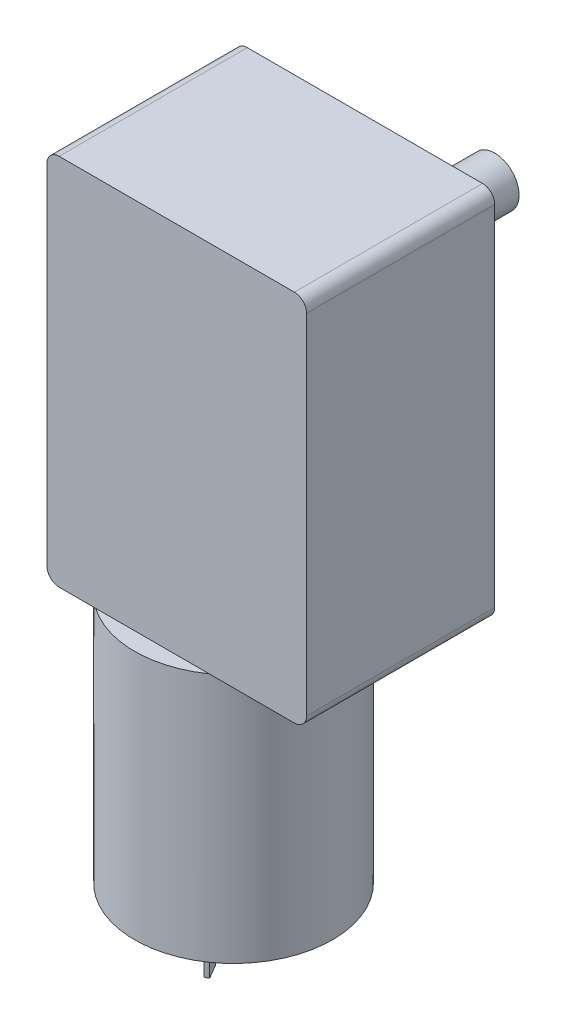
SolidWorks part; units mm, degrees
ref_plane "Front Plane" through (0, 0, 0) normal (0, 0, 1) x (1, 0, 0)
ref_plane "Top Plane" through (0, 0, 0) normal (0, 1, 0) x (1, 0, 0)
ref_plane "Right Plane" through (0, 0, 0) normal (1, 0, 0) x (0, 0, -1)
sketch "Sketch1" plane through (0, 0, 0) normal (0, 0, 1) x (1, 0, 0)
  line L1 (-16, 15) -> (16, 15)
  line L2 (-16, 15) -> (-16, -31)
  line L3 (-16, -31) -> (16, -31)
  line L4 (16, 15) -> (16, -31)
  circle A0 centre (-11.1667, 9) radius 1.5 construction
  circle A1 centre (12.1667, 9) radius 1.5 construction
  circle A2 centre (-11.1667, -24) radius 1.5 construction
  circle A3 centre (12.1667, -24) radius 1.5 construction
  circle A4 centre (0, 0) radius 3 construction
  dimension "D4" = 3
  dimension "D1" = 32
  dimension "D2" = 46
  dimension "D3" = 9
  dimension "D5" = 6
  dimension "D6" = 33
extrude "Boss-Extrude1" add sketch "Sketch1" along normal blind 23.2
sketch "Sketch2" plane through (0, 0, 0) normal (0, 0, -1) x (-1, 0, 0)
  line L0 (0, 0) -> (0, -17.9583) construction
  line L1 (-5, -13) -> (5, -13) construction
  line L2 (-5, -10) -> (5, -10)
  line L3 (-5, -16) -> (5, -16)
  circle A0 centre (-9, 9) radius 3.85
  circle A1 centre (9, 9) radius 3.85
  circle A2 centre (-9, -24) radius 3.85
  circle A3 centre (9, -24) radius 3.85
  circle A4 centre (0, 0) radius 6.65
  arc A5 (-5, -10) -> (-5, -16) centre (-5, -13) ccw
  arc A6 (5, -16) -> (5, -10) centre (5, -13) ccw
  point P3 (0, -13)
  dimension "D1" = 7.7
  dimension "D4" = 13.3
  dimension "D2" = 18
  dimension "D3" = 9
  dimension "D5" = 13
  dimension "D6" = 10
extrude "Boss-Extrude2" add sketch "Sketch2" along normal blind 2
sketch "Sketch3" plane through (0, 0, -2) normal (0, 0, -1) x (-1, 0, 0)
  circle A0 centre (9, 9) radius 1.5
  circle A1 centre (-9, 9) radius 1.5
  circle A2 centre (-9, -24) radius 1.5
  circle A3 centre (9, -24) radius 1.5
extrude "Cut-Extrude1" cut sketch "Sketch3" against normal blind 4 contours A0 | A1 | A2 | A3
sketch "Sketch4" plane through (0, 0, -2) normal (0, 0, -1) x (-1, 0, 0)
  circle A0 centre (0, 0) radius 3
extrude "Boss-Extrude3" add sketch "Sketch4" along normal blind 14
sketch "Sketch5" plane through (0, 0, -16) normal (0, 0, -1) x (-1, 0, 0)
  line L0 (2.5, -1.6583) -> (2.5, 1.6583)
  line L1 (-3, 2.7789) -> (-3, -6.1307) construction
  circle A1 centre (0, 0) radius 3
  circle A2 centre (0, 0) radius 3 construction
  circle M3 centre (0, 0) radius 3
  dimension "D1" = 5.5
  dimension "D2" = 2.5
extrude "Cut-Extrude2" cut sketch "Sketch5" against normal blind 12 contours L0 M3
fillet "Fillet1" radius 1.5 4 edges at (16, 15, 11.6) (-16, 15, 11.6) (-16, -31, 11.6) (16, -31, 11.6)
sketch "Sketch6" plane through (0, -31, 0) normal (0, -1, 0) x (1, 0, 0)
  line L0 (0, -0.7119) -> (0, 27.8804) construction
  line L1 (-18.7162, 11.6) -> (20.0738, 11.6) construction
  line L2 (-14.5, 0) -> (14.5, 0) construction
  line L3 (-14.5, 23.2) -> (14.5, 23.2) construction
  line L6 (3.811, 1) -> (-11.4645, 1) construction
  circle A0 centre (-3, 13.2) radius 12.2
  dimension "D1" = 24.4
  dimension "D2" = 1
  dimension "D3" = 3
extrude "Boss-Extrude4" add sketch "Sketch6" along normal blind 30.8
sketch "Sketch7" plane through (0, -61.8, 0) normal (0, -1, 0) x (1, 0, 0)
  circle A0 centre (-3, 13.2) radius 3.2
  dimension "D1" = 6.4
extrude "Boss-Extrude5" add sketch "Sketch7" along normal blind 2.2
fillet "Fillet2" radius 1 1 edges at (-3, -64, 10)
sketch "Sketch8" plane through (0, -61.8, 0) normal (0, -1, 0) x (1, 0, 0)
  line L0 (3.9875, 25.3026) -> (-9.6131, 1.7457) construction
  line L1 (-3, 13.2) -> (-16.9171, 13.2) construction
  line L2 (1.2676, 21.0917) -> (0.2994, 19.4147)
  line L3 (1.7006, 20.8417) -> (0.7324, 19.1647)
  line L4 (4.204, 25.1776) -> (-9.3966, 1.6207) construction
  line L5 (-6.2994, 6.9853) -> (-7.2676, 5.3083)
  line L6 (-6.7324, 7.2353) -> (-7.7006, 5.5583)
  line L7 (3.7709, 25.4276) -> (-9.8296, 1.8707) construction
  arc A2 (-6.2994, 6.9853) -> (-6.7324, 7.2353) centre (-7, 6.2718) ccw
  arc A3 (0.2994, 19.4147) -> (0.7324, 19.1647) centre (1, 20.1282) ccw
  arc A4 (-7.7006, 5.5583) -> (-7.2676, 5.3083) centre (-7, 6.2718) ccw
  arc A5 (1.7006, 20.8417) -> (1.2676, 21.0917) centre (1, 20.1282) ccw
  dimension "D2" = 2
  dimension "D1" = 60
  dimension "D5" = 8
  dimension "D6" = 8
  dimension "D3" = 0.25
  dimension "D4" = 0.25
extrude "Boss-Extrude6" add sketch "Sketch8" along normal blind 4
